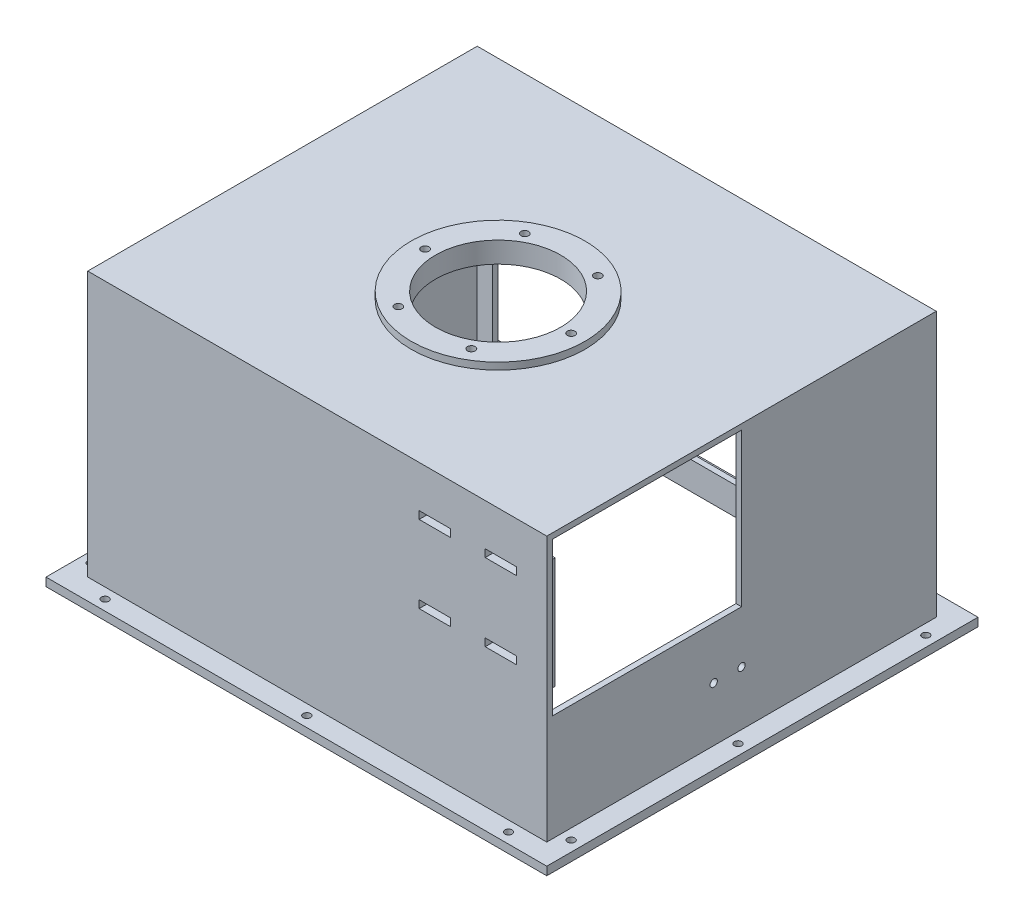
SolidWorks part; units mm, degrees
ref_plane "Piano frontale" through (0, 0, 0) normal (0, 0, 1) x (1, 0, 0)
ref_plane "Piano superiore" through (0, 0, 0) normal (0, 1, 0) x (1, 0, 0)
ref_plane "Piano destro" through (0, 0, 0) normal (1, 0, 0) x (0, 0, -1)
sketch "Schizzo1" plane through (0, 0, 0) normal (0, 1, 0) x (1, 0, 0)
  line L1 (0, 0) -> (720, 0)
  line L2 (0, 0) -> (0, 620)
  line L3 (0, 620) -> (720, 620)
  line L4 (720, 0) -> (720, 620)
  dimension "D1" = 720
  dimension "D2" = 620
extrude "Estrusione-Estrusione1" add sketch "Schizzo1" along normal blind 393
sketch "Schizzo3" plane through (0, 393, 0) normal (0, 1, 0) x (1, 0, 0)
  line L1 (30, 30) -> (690, 30)
  line L2 (0, 0) -> (30, 0)
  line L3 (0, 0) -> (720, 0) construction
  line L4 (30, 0) -> (30, 30) construction
  line L5 (30, 30) -> (30, 590)
  line L6 (30, 590) -> (690, 590)
  line L7 (690, 30) -> (690, 590)
  line L8 (0, 0) -> (720, 0)
  line L9 (0, 0) -> (0, 620)
  line L10 (0, 620) -> (720, 620)
  line L11 (720, 0) -> (720, 620)
  dimension "D1" = 30
  dimension "D2" = 30
  dimension "D3" = 660
  dimension "D4" = 560
extrude "Taglio-Estrusione1" cut sketch "Schizzo3" against normal blind 381
sketch "Schizzo4" plane through (0, 12, 0) normal (0, 1, 0) x (1, 0, 0)
  line L0 (360, 0) -> (360, 620) construction
  line L1 (0, 0) -> (720, 0) construction
  line L2 (720, 620) -> (0, 620) construction
  line L3 (0, 310) -> (720, 310) construction
  line L4 (360, 605) -> (650, 605) construction
  line L5 (705, 605) -> (705, 560) construction
  line L6 (0, 620) -> (0, 0) construction
  line L7 (720, 0) -> (720, 620) construction
  line L8 (360, 620) -> (360, 590) construction
  line L9 (30, 590) -> (690, 590) construction
  line L10 (360, 605) -> (705, 605) construction
  line L11 (705, 560) -> (705, 290) construction
  line L12 (705, 290) -> (705, 50) construction
  circle A0 centre (360, 605) radius 5.25
  circle A1 centre (650, 605) radius 5.25
  circle A2 centre (70, 605) radius 5.25
  circle A3 centre (650, 15) radius 5.25
  circle A4 centre (360, 15) radius 5.25
  circle A5 centre (70, 15) radius 5.25
  circle A6 centre (705, 560) radius 5.25
  circle A7 centre (705, 290) radius 5.25
  circle A8 centre (705, 50) radius 5.25
  circle A9 centre (15, 50) radius 5.25
  circle A10 centre (15, 290) radius 5.25
  circle A11 centre (15, 560) radius 5.25
  dimension "D2" = 10.5
  dimension "D4" = 10.5
  dimension "D9" = 10.5
  dimension "D10" = 10.5
  dimension "D11" = 10.5
  dimension "D1" = 345
  dimension "D3" = 290
  dimension "D5" = 295
  dimension "D6" = 45
  dimension "D7" = 270
  dimension "D8" = 240
extrude "Taglio-Estrusione2" cut sketch "Schizzo4" against normal up to surface (12 mm away) up to face at (360, 0, -310)
sketch "Schizzo5" plane through (0, 0, 0) normal (0, 1, 0) x (1, 0, 0)
  line L0 (0, 620) -> (38, 620) construction
  line L1 (720, 620) -> (0, 620) construction
  line L2 (38, 620) -> (38, 582) construction
  line L4 (38, 582) -> (682, 582)
  line L5 (38, 582) -> (38, 38)
  line L6 (38, 38) -> (682, 38)
  line L7 (682, 582) -> (682, 38)
  dimension "D1" = 38
  dimension "D2" = 38
  dimension "D3" = 644
  dimension "D4" = 544
extrude "Taglio-Estrusione3" cut sketch "Schizzo5" along normal blind 385
sketch "Schizzo6" plane through (0, 393, 0) normal (0, 1, 0) x (1, 0, 0)
  line L0 (15, 290) -> (705, 290) construction
  circle A2 centre (360, 290) radius 125
  dimension "D1" = 250
extrude "Estrusione-Estrusione2" add sketch "Schizzo6" along normal blind 10 and the other way blind 20
sketch "Schizzo7" plane through (0, 403, 0) normal (0, 1, 0) x (1, 0, 0)
  line L0 (15, 290) -> (705, 290) construction
  circle A0 centre (360, 290) radius 90
  dimension "D1" = 180
extrude "Taglio-Estrusione4" cut sketch "Schizzo7" against normal up to surface (30 mm away) up to face at (360, 373, -165)
hole_wizard "Foro per Vite M10-1" positions "Schizzo3D1" profile "Schizzo12" hole size "M10" standard "ISO"
sketch3d "Schizzo3D1"
  line L0 (360, 403, -290) -> (465, 403, -290) construction
  line L1 (360, 373, -290) -> (360, 403, -290) construction
  line L2 (360, 393, -290) -> (360, 403, -290) construction
  point P0 (465, 403, -290)
  dimension "D1" = 105
sketch "Schizzo12" plane through (465, 403, -290) normal (1, 0, 0) x (0, 0, 1)
  line L0 (0, 0) -> (0, 33.3037)
  line L1 (0, 33.3037) -> (5.5, 29.999)
  line L2 (5.5, 29.999) -> (5.5, 0)
  line L5 (5.5, 0) -> (0, 0)
  line L10 (0, 33.3037) -> (-5.5, 29.999) construction
  line L11 (0, -6.35) -> (0, 107.95) construction
  dimension "Hole Dia." = 11
  dimension "Hole Depth" = 29.999
  dimension "Drill Angle" = 118
pattern_circular "RipetizioneCircolare1" count 6 over 360 about axis through (360, 0, -290) along (0, 1, 0) of "Foro per Vite M10-1"
sketch "Schizzo14" plane through (0, 0, -582) normal (0, 0, 1) x (1, 0, 0)
  line L0 (0, 0) -> (0, 40) construction
  line L1 (0, 40) -> (60, 40) construction
  line L3 (60, 40) -> (660, 40)
  line L4 (60, 40) -> (60, 340)
  line L5 (60, 340) -> (660, 340)
  line L6 (660, 40) -> (660, 340)
  dimension "D1" = 40
  dimension "D2" = 60
  dimension "D3" = 600
  dimension "D4" = 300
extrude "Taglio-Estrusione5" cut sketch "Schizzo14" against normal up to surface (8 mm away) up to face at (360, 202.5, -590)
sketch "Schizzo16" plane through (30, 0, 0) normal (-1, 0, 0) x (0, 0, 1)
  line L0 (-620, 0) -> (-620, 90) construction
  line L1 (-620, 90) -> (-310, 90) construction
  line L2 (-310, 90) -> (-270, 90) construction
  circle A0 centre (-310, 90) radius 5.25
  circle A1 centre (-270, 90) radius 5.25
  dimension "D4" = 10.5
  dimension "D5" = 10.5
  dimension "D1" = 90
  dimension "D2" = 310
  dimension "D3" = 40
extrude "Taglio-Estrusione6" cut sketch "Schizzo16" against normal up to surface (8 mm away) up to face at (38, 192.5, -310)
sketch "Schizzo17" plane through (690, 0, 0) normal (1, 0, 0) x (0, 0, -1)
  line L0 (620, 0) -> (620, 90) construction
  line L1 (620, 90) -> (310, 90) construction
  line L2 (310, 90) -> (270, 90) construction
  circle A0 centre (310, 90) radius 5.25
  circle A1 centre (270, 90) radius 5.25
  dimension "D4" = 10.5
  dimension "D5" = 10.5
  dimension "D1" = 90
  dimension "D2" = 310
  dimension "D3" = 40
extrude "Taglio-Estrusione7" cut sketch "Schizzo17" against normal up to surface (8 mm away) up to face at (682, 192.5, -310)
sketch "Schizzo18" plane through (682, 0, 0) normal (-1, 0, 0) x (0, 0, 1)
  line L1 (-38, 385) -> (-310, 385)
  line L2 (-38, 385) -> (-38, 165)
  line L3 (-38, 165) -> (-310, 165)
  line L4 (-310, 385) -> (-310, 165)
  dimension "D1" = 220
  dimension "D2" = 272
extrude "Taglio-Estrusione8" cut sketch "Schizzo18" against normal up to surface (8 mm away) up to face at (690, 90, -315.25)
sketch "Schizzo19" plane through (0, 0, -38) normal (0, 0, -1) x (-1, 0, 0)
  line L0 (-682, 0) -> (-682, 192) construction
  line L1 (-682, 385) -> (-682, 165) construction
  line L3 (-682, 192) -> (-482, 192)
  line L4 (-682, 192) -> (-682, 352)
  line L5 (-682, 352) -> (-482, 352)
  line L6 (-482, 192) -> (-482, 352)
  dimension "D1" = 192
  dimension "D2" = 200
  dimension "D3" = 160
extrude "Estrusione-Estrusione3" add sketch "Schizzo19" along normal blind 12
sketch "Schizzo20" plane through (0, 0, -50) normal (0, 0, -1) x (-1, 0, 0)
  line L0 (-690, 272) -> (-624, 272) construction
  line L1 (-646.5, 222) -> (-601.5, 222)
  line L2 (-690, 385) -> (-690, 165) construction
  line L3 (-624, 272) -> (-529, 272) construction
  line L4 (-682, 0) -> (-682, 216.5) construction
  line L5 (-682, 352) -> (-682, 192) construction
  line L6 (-682, 216.5) -> (-624, 216.5) construction
  line L7 (-624, 216.5) -> (-529, 216.5) construction
  line L8 (-624, 216.5) -> (-624, 222) construction
  line L9 (-646.5, 222) -> (-646.5, 211)
  line L10 (-646.5, 211) -> (-601.5, 211)
  line L11 (-601.5, 211) -> (-601.5, 222)
  line L12 (-529, 216.5) -> (-529, 222) construction
  line L13 (-551.5, 222) -> (-506.5, 222)
  line L14 (-551.5, 222) -> (-551.5, 211)
  line L15 (-551.5, 211) -> (-506.5, 211)
  line L16 (-506.5, 211) -> (-506.5, 222)
  line L17 (-551.5, 322) -> (-506.5, 322)
  line L18 (-506.5, 333) -> (-506.5, 322)
  line L19 (-551.5, 333) -> (-506.5, 333)
  line L20 (-551.5, 322) -> (-551.5, 333)
  line L21 (-646.5, 322) -> (-646.5, 333)
  line L22 (-646.5, 333) -> (-601.5, 333)
  line L23 (-601.5, 333) -> (-601.5, 322)
  line L24 (-646.5, 322) -> (-601.5, 322)
  point P15 (-624, 222)
  point P21 (-529, 222)
  dimension "D1" = 272
  dimension "D2" = 5.5
  dimension "D3" = 216.5
  dimension "D4" = 95
  dimension "D5" = 58
  dimension "D6" = 45
  dimension "D7" = 11
  dimension "D8" = 45
  dimension "D9" = 11
  dimension "D10" = 5.5
extrude "Taglio-Estrusione9" cut sketch "Schizzo20" against normal up to surface (20 mm away) up to face at (360, 202.5, -30)
